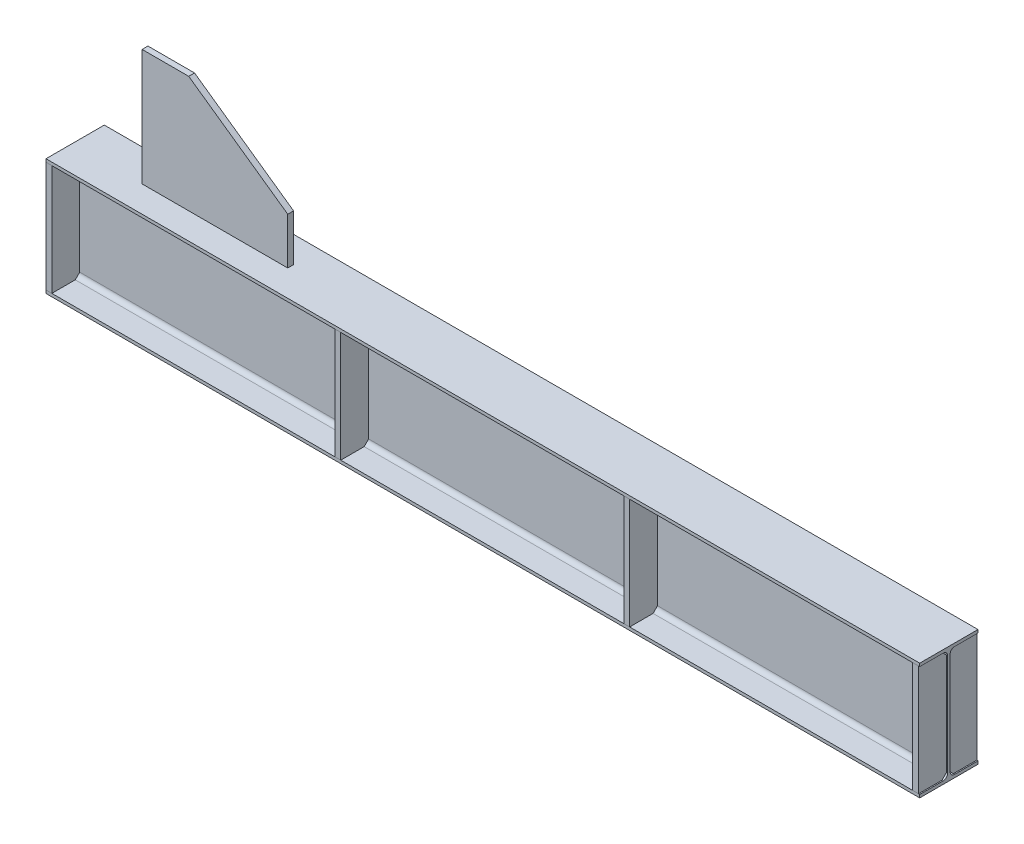
SolidWorks part; units mm, degrees
ref_plane "Alzado" through (0, 0, 0) normal (0, 0, 1) x (1, 0, 0)
ref_plane "Planta" through (0, 0, 0) normal (0, 1, 0) x (1, 0, 0)
ref_plane "Vista lateral" through (0, 0, 0) normal (1, 0, 0) x (0, 0, -1)
sketch "Croquis1" plane through (0, 0, 0) normal (0, 1, 0) x (1, 0, 0)
  line L0 (-750, 0) -> (750, 0)
  point P4 (0, 0)
  dimension "D1" = 1500
other "W section W8X10(1)"
ref_plane "Plano1" through (-750, 0, 0) normal (1, 0, 0) x (0, 0, -1)
sketch "Sketch1" plane through (-750, 0, 0) normal (1, 0, 0) x (0, 0, -1)
  line L0 (-50.038, -100.203) -> (-50.038, -94.996)
  line L1 (-50.038, -94.996) -> (-9.779, -94.996)
  line L2 (-2.159, -87.376) -> (-2.159, 87.376)
  line L3 (-9.779, 94.996) -> (-50.038, 94.996)
  line L4 (-50.038, 94.996) -> (-50.038, 100.203)
  line L5 (-50.038, 100.203) -> (50.038, 100.203)
  line L6 (50.038, 100.203) -> (50.038, 94.996)
  line L7 (50.038, 94.996) -> (9.779, 94.996)
  line L8 (2.159, 87.376) -> (2.159, -87.376)
  line L9 (9.779, -94.996) -> (50.038, -94.996)
  line L10 (50.038, -94.996) -> (50.038, -100.203)
  line L11 (50.038, -100.203) -> (-50.038, -100.203)
  line L12 (0, 0) -> (0, 100.203) construction
  line L13 (-2.159, 0) -> (2.159, 0) construction
  arc A0 (-9.779, -94.996) -> (-2.159, -87.376) centre (-9.779, -87.376) ccw
  arc A1 (-2.159, 87.376) -> (-9.779, 94.996) centre (-9.779, 87.376) ccw
  arc A2 (9.779, 94.996) -> (2.159, 87.376) centre (9.779, 87.376) ccw
  arc A3 (2.159, -87.376) -> (9.779, -94.996) centre (9.779, -87.376) ccw
  point P23 (0, 0)
  point P26 (0, -100.203)
  dimension "Ri" = 7.62
  dimension "D1" = 2.159
  dimension "D2" = 5.207
  dimension "Tw" = 4.318
  dimension "Bf" = 100.076
  dimension "Depth" = 200.406
  dimension "Tf" = 5.207
sketch "Croquis8" plane through (-750, 0, 0) normal (-1, 0, 0) x (0, 0, 1)
  line L0 (-50.038, 94.996) -> (-9.779, 94.996)
  line L1 (-9.779, 94.996) -> (-2.159, 87.376)
  line L2 (-2.159, -87.376) -> (-2.159, 87.376) construction
  line L3 (-2.159, 87.376) -> (-2.159, -87.376)
  line L4 (-2.159, -87.376) -> (-9.779, -94.996)
  line L5 (-9.779, -94.996) -> (-50.038, -94.996)
  line L6 (-50.038, -94.996) -> (-50.038, 94.996)
  arc A0 (-2.159, 87.376) -> (-9.779, 94.996) centre (-9.779, 87.376) ccw construction
extrude "Saliente-Extruir1" add sketch "Croquis8" against normal blind 10 separate body
pattern_linear "MatrizL2" count 4 spacing 496 along (1, 0, 0) of bodies 102
sketch "Croquis9" plane through (0, 0, 0) normal (0, 0, 1) x (1, 0, 0)
  line L0 (-630, 100.203) -> (-630, 300.203)
  line L1 (750, 100.203) -> (-750, 100.203) construction
  line L2 (-630, 300.203) -> (-550, 300.203)
  line L3 (-550, 300.203) -> (-380, 180.203)
  line L4 (-380, 180.203) -> (-380, 100.203)
  line L5 (-380, 100.203) -> (-630, 100.203)
  line L6 (-750, 87.376) -> (-750, -87.376) construction
  dimension "D1" = 250
  dimension "D2" = 200
  dimension "D3" = 80
  dimension "D4" = 80
  dimension "D5" = 120
extrude "Saliente-Extruir2" add sketch "Croquis9" along normal mid plane 10 separate body
mirror "Simetría1" about plane through (0, 0, 0) normal (0, 0, 1) of bodies 105 104 103 102
